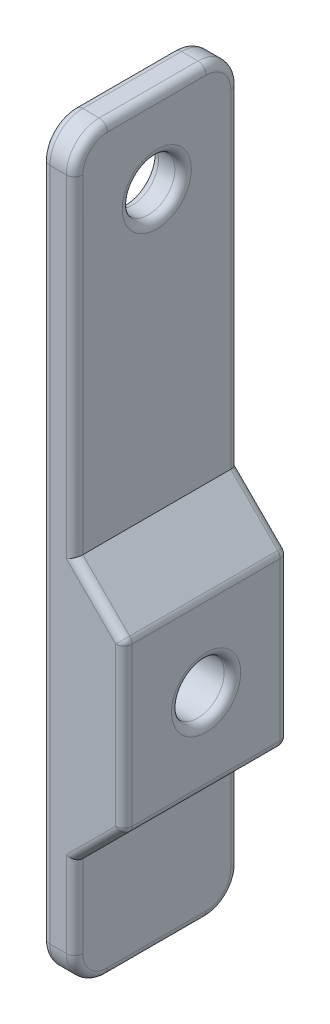
SolidWorks part; units mm, degrees
ref_plane "Спереди" through (0, 0, 0) normal (0, 0, 1) x (1, 0, 0)
ref_plane "Сверху" through (0, 0, 0) normal (0, 1, 0) x (1, 0, 0)
ref_plane "Справа" through (0, 0, 0) normal (1, 0, 0) x (0, 0, -1)
sketch "Эскиз1" plane through (0, 0, 0) normal (0, 0, 1) x (1, 0, 0)
  line L0 (0, 0) -> (2, 0)
  line L1 (2, 0) -> (2, 7)
  line L2 (2, 7) -> (5, 10)
  line L3 (5, 10) -> (5, 20)
  line L4 (5, 20) -> (2, 23)
  line L5 (2, 23) -> (2, 45)
  line L6 (2, 45) -> (0, 45)
  line L7 (0, 45) -> (0, 0)
  point P3 (5, 15)
  dimension "D1" = 2
  dimension "D2" = 10
  dimension "D3" = 45
  dimension "D4" = 3
  dimension "D5" = 45
  dimension "D6" = 30
extrude "Бобышка-Вытянуть1" add sketch "Эскиз1" along normal blind 10
sketch "Эскиз2" plane through (0, 0, 0) normal (-1, 0, 0) x (0, 0, 1)
  line L0 (10, 0) -> (0, 0) construction
  line L1 (5, -2.1353) -> (5, 51.0734) construction
  line L2 (10, 45) -> (0, 45) construction
  circle A0 centre (5, 15) radius 1.6
  circle A1 centre (5, 40) radius 1.6
  point P0 (5, 0)
  dimension "D3" = 3.2
  dimension "D1" = 30
  dimension "D2" = 5
extrude "Вырез-Вытянуть1" cut sketch "Эскиз2" against normal through all
fillet "Скругление8" radius 0.5 8 edges at (3.5, 21.5, 10) (3.5, 21.5, 0) (3.5, 8.5, 10) (3.5, 8.5, 0) (5, 15, 0) (5, 10, 5) (5, 15, 10) (5, 20, 5)
fillet "Скругление6" radius 2 4 edges at (1, 45, 0) (1, 45, 10) (1, 0, 10) (1, 0, 0)
fillet "Скругление9" radius 0.5 18 edges at (0, 44.4142, 0.5858) (0, 45, 5) (0, 44.4142, 9.4142) (0, 22.5, 10) (0, 0.5858, 9.4142) (0, 0, 5) (0, 0.5858, 0.5858) (2, 32.6464, 10) (2, 44.4142, 9.4142) (2, 32.6464, 0) (2, 44.4142, 0.5858) (2, 4.8536, 10) (2, 0.5858, 9.4142) (2, 4.8536, 0) (2, 0.5858, 0.5858) (0, 22.5, 0) (2, 45, 5) (2, 0, 5)
fillet "Скругление10" radius 0.5 4 edges at (0, 13.4, 5) (5, 13.4, 5) (2, 38.4, 5) (0, 38.4, 5)
equation "\"D5@Эскиз1\"=45"
